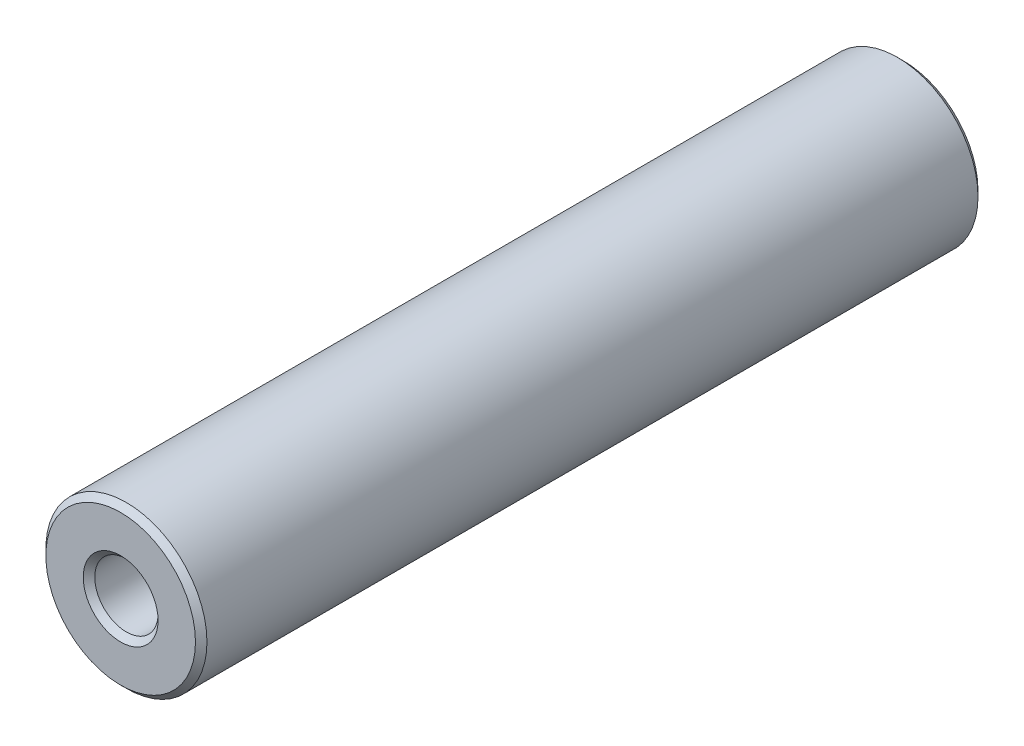
SolidWorks part; units mm, degrees
material "AISI 4140 Steel, quenched & tempered"
ref_plane "Front Plane" through (0, 0, 0) normal (1, 0, 0) x (0, 1, 0)
ref_plane "Top Plane" through (0, 0, 0) normal (0, 0, 1) x (0, 1, 0)
ref_plane "Right Plane" through (0, 0, 0) normal (0, 1, 0) x (-1, 0, 0)
sketch "Sketch1" plane through (0, 0, 0) normal (0, 0, 1) x (0, 1, 0)
  circle A0 centre (0, 0) radius 7
  circle A1 centre (0, 0) radius 2.75
  dimension "D1" = 14
  dimension "D2" = 5.5
extrude "Boss-Extrude1" add sketch "Sketch1" along normal mid plane 68
chamfer "Chamfer1" distance 0.5 angle 45 2 edges at (2.75, 0, -34) (2.75, 0, 34)
chamfer "Chamfer2" distance 0.5 angle 45 2 edges at (7, 0, -34) (7, 0, 34)
